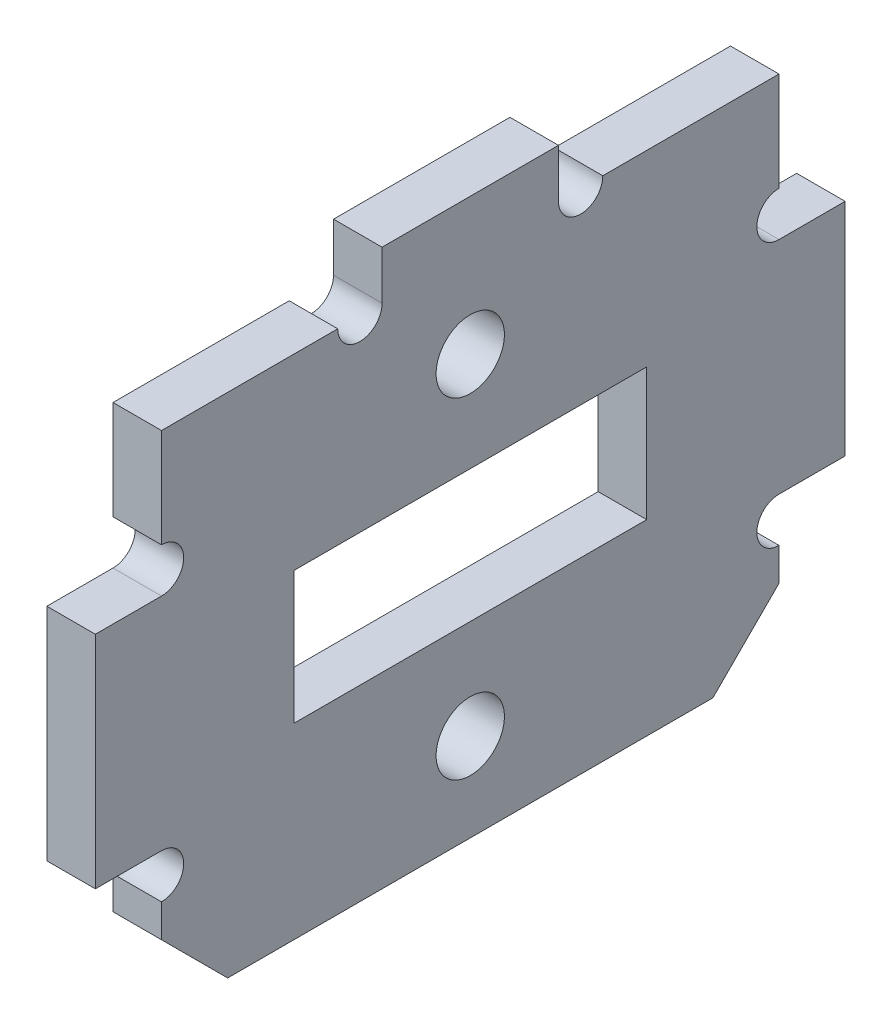
SolidWorks part; units mm, degrees
material "Thornel Mat VMA"
ref_plane "前视基准面" through (0, 0, 0) normal (0, 0, 1) x (1, 0, 0)
ref_plane "上视基准面" through (0, 0, 0) normal (0, 1, 0) x (1, 0, 0)
ref_plane "右视基准面" through (0, 0, 0) normal (1, 0, 0) x (0, 0, -1)
sketch "草图1" plane through (0, 0, 0) normal (1, 0, 0) x (0, 0, -1)
  line L0 (0, 0) -> (0, 13.7) construction
  line L1 (14, -11.5) -> (-14, -11.5)
  line L2 (14, -11.5) -> (14, -5)
  line L3 (14, 11.5) -> (4, 11.5)
  line L4 (-14, -11.5) -> (-14, -5)
  line L5 (14, -11.5) -> (-14, 11.5) construction
  line L6 (14, 11.5) -> (-14, -11.5) construction
  line L7 (-4, 11.5) -> (-4, 13.7)
  line L8 (-4, 13.7) -> (4, 13.7)
  line L9 (4, 13.7) -> (4, 11.5)
  line L10 (0, 0) -> (5.3139, 0) construction
  line L11 (-4, 11.5) -> (-14, 11.5)
  line L12 (-14, 5) -> (-17, 5)
  line L13 (-17, 5) -> (-17, -5)
  line L14 (-17, -5) -> (-14, -5)
  line L15 (-14, 5) -> (-14, 11.5)
  line L16 (17, -5) -> (14, -5)
  line L17 (17, 5) -> (17, -5)
  line L18 (14, 5) -> (17, 5)
  line L19 (14, 5) -> (14, 11.5)
  line L21 (8, -3) -> (-8, -3)
  line L22 (8, -3) -> (8, 3)
  line L23 (8, 3) -> (-8, 3)
  line L24 (-8, -3) -> (-8, 3)
  line L25 (8, -3) -> (-8, 3) construction
  line L26 (8, 3) -> (-8, -3) construction
  circle A0 centre (0, 7.5) radius 1.55
  circle A1 centre (0, -7.5) radius 1.55
  circle A2 centre (5.005, 11.5) radius 1.005
  circle A3 centre (-5.005, 11.5) radius 1.005
  circle A4 centre (-14, 6.005) radius 1.005
  circle A5 centre (-14, -6.005) radius 1.005
  circle A6 centre (14, -6.005) radius 1.005
  circle A7 centre (14, 6.005) radius 1.005
  point P0 (0, 0)
  dimension "D5" = 3.1
  dimension "D7" = 2.01
  dimension "D10" = 2.01
  dimension "D1" = 28
  dimension "D2" = 8
  dimension "D3" = 2.2
  dimension "D4" = 15
  dimension "D6" = 4
  dimension "D8" = 3
  dimension "D9" = 10
  dimension "D11" = 16
  dimension "D12" = 4.5
extrude "凸台-拉伸1" add sketch "草图1" along normal blind 2.2 contours A3 L11 L4 L1 L2 L3 A2 L9 L8 L7 A0 A1
chamfer "倒角1" distance 3 angle 45 2 edges at (1.1, -11.5, -14) (1.1, -11.5, 14)
